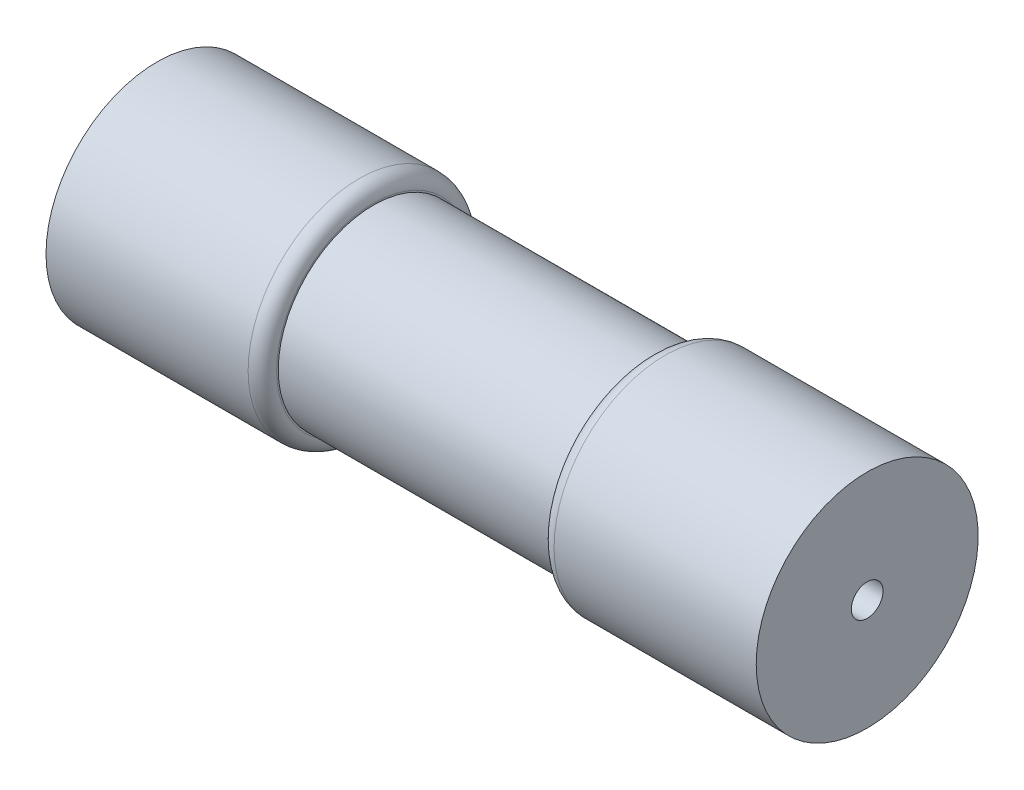
SolidWorks part; units mm, degrees
ref_plane "Plan de face" through (0, 0, 0) normal (0, 0, 1) x (1, 0, 0)
ref_plane "Plan de dessus" through (0, 0, 0) normal (0, 1, 0) x (1, 0, 0)
ref_plane "Plan de droite" through (0, 0, 0) normal (1, 0, 0) x (0, 0, -1)
sketch "Esquisse1" plane through (0, 0, 0) normal (0, 0, 1) x (1, 0, 0)
  line L0 (0, 0) -> (448, 0) construction
  line L1 (0, 0) -> (0, 70)
  line L2 (0, 70) -> (127.5, 70)
  line L3 (136.5, 61) -> (136.5, 60)
  line L4 (136.5, 60) -> (311.5, 60)
  line L5 (311.5, 60) -> (311.5, 61)
  line L6 (320.5, 70) -> (448, 70)
  line L7 (448, 70) -> (448, 0)
  line L8 (0, 0) -> (448, 0)
  line L10 (0, 0) -> (448, 0)
  line L11 (0, 0) -> (0, 10)
  line L12 (0, 10) -> (448, 10)
  line L13 (448, 0) -> (448, 10)
  arc A0 (127.5, 70) -> (136.5, 61) centre (127.5, 61) cw
  arc A1 (311.5, 61) -> (320.5, 70) centre (320.5, 61) cw
  dimension "D1" = 140
  dimension "D2" = 448
  dimension "D3" = 175
  dimension "D4" = 1
  dimension "D5" = 120
  dimension "D6" = 10
revolve "Révolution1" add sketch "Esquisse1" angle 360 about L0
